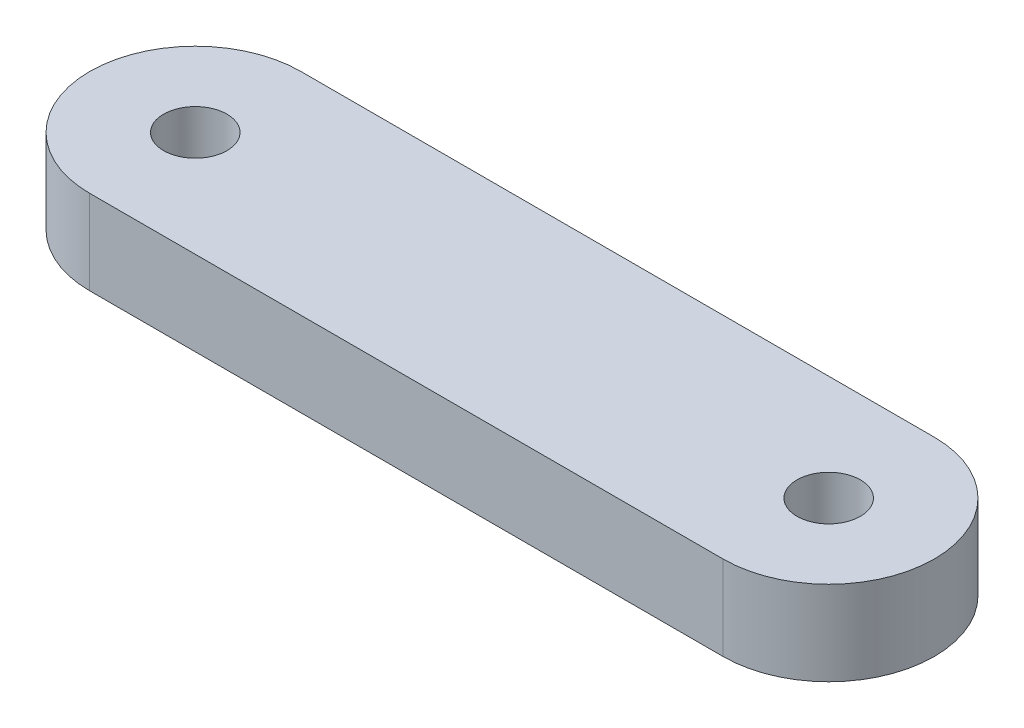
SolidWorks part; units mm, degrees
ref_plane "前视基准面" through (0, 0, 0) normal (0, 0, 1) x (1, 0, 0)
ref_plane "上视基准面" through (0, 0, 0) normal (0, 1, 0) x (1, 0, 0)
ref_plane "右视基准面" through (0, 0, 0) normal (1, 0, 0) x (0, 0, -1)
other "Configuration Table"
sketch "草图1" plane through (0, 0, 0) normal (0, 1, 0) x (1, 0, 0)
  line L0 (0, 0) -> (300, 0) construction
  line L1 (0, 50) -> (300, 50)
  line L2 (0, -50) -> (300, -50)
  arc A0 (0, 50) -> (0, -50) centre (0, 0) ccw
  arc A1 (300, -50) -> (300, 50) centre (300, 0) ccw
  circle A2 centre (0, 0) radius 15
  circle A3 centre (300, 0) radius 15
  point P3 (150, 0)
  dimension "D2" = 50
  dimension "D3" = 30
  dimension "D4" = 30
  dimension "D1" = 300
extrude "凸台-拉伸1" add sketch "草图1" along normal blind 80
sketch "草图2" plane through (0, 0, 50) normal (0, 0, 1) x (1, 0, 0)
  line L0 (0, 80) -> (300, 80) construction
  line L1 (-100, 100) -> (400, 100)
  line L2 (-100, 100) -> (-100, 60)
  line L3 (-100, 60) -> (400, 60)
  line L4 (400, 100) -> (400, 60)
  line L5 (0, 80) -> (0, 0) construction
  line L18 (-100, 20) -> (400, 20)
  line L19 (-100, 20) -> (-100, -20)
  line L20 (-100, -20) -> (400, -20)
  line L21 (400, 20) -> (400, -20)
  dimension "D1" = 40
  dimension "D2" = 20
  dimension "D3" = 500
  dimension "D4" = 400
  dimension "D9" = 500
  dimension "D10" = 40
  dimension "D13" = 40
  dimension "D15" = 400
extrude "切除-拉伸3" cut sketch "草图2" against normal blind 120
